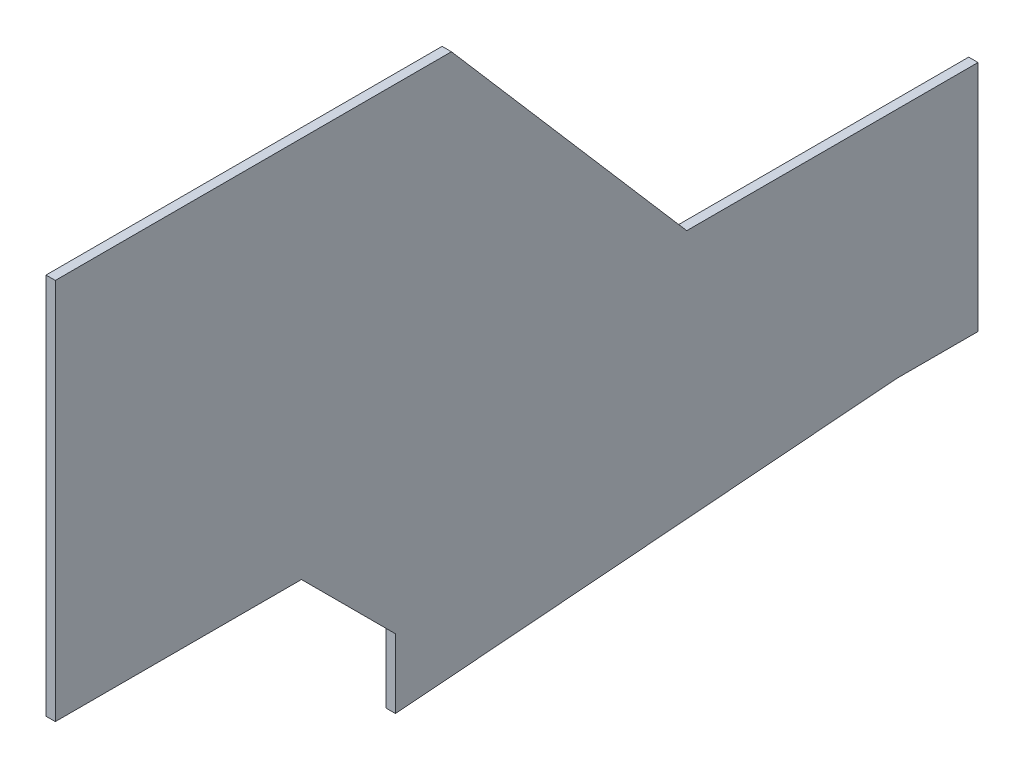
SolidWorks part; units mm, degrees
ref_plane "Alzado" through (0, 0, 0) normal (0, 0, 1) x (1, 0, 0)
ref_plane "Planta" through (0, 0, 0) normal (0, 1, 0) x (1, 0, 0)
ref_plane "Vista lateral" through (0, 0, 0) normal (1, 0, 0) x (0, 0, -1)
sketch "Croquis2" plane through (0, 0, 0) normal (1, 0, 0) x (0, 0, -1)
  line L0 (-196, -75) -> (-90.3534, -75)
  line L1 (-200, 150) -> (200, 150) construction
  line L2 (-200, 150) -> (-200, -150) construction
  line L3 (-200, -150) -> (200, -150) construction
  line L4 (200, 150) -> (200, -150) construction
  line L5 (-200, 150) -> (200, -150) construction
  line L6 (-200, -150) -> (200, 150) construction
  line L11 (-90.3534, -75) -> (-28.5398, -75) construction
  line L12 (-150, -75) -> (-150, -79) construction
  line L17 (-90.3534, -75) -> (-50, -115.3534)
  line L18 (-50, -115.3534) -> (-50, -145)
  line L19 (-50, -145) -> (165, -128)
  line L20 (165, -128) -> (200, -128)
  line L21 (200, -128) -> (200, -28)
  line L22 (200, -28) -> (75, -28)
  line L23 (75, -28) -> (-26, 89)
  line L24 (-26, 89) -> (-196, 89)
  line L25 (-196, 89) -> (-196, -75)
  line L26 (-150, -79) -> (-100, -79) construction
  line L27 (-100, -79) -> (-100, -75) construction
  point P0 (0, 0)
  point P9 (-98.3041, -71)
  point P10 (2, 0)
  dimension "D1" = 400
  dimension "D2" = 300
  dimension "D3" = 4
  dimension "D4" = 75
  dimension "D6" = 22
  dimension "D7" = 35
  dimension "D5" = 5
  dimension "D8" = 150
  dimension "D9" = 45
  dimension "D10" = 100
  dimension "D11" = 170
  dimension "D12" = 275
  dimension "D13" = 164
  dimension "D14" = 50
  dimension "D15" = 4
  dimension "D16" = 50
extrude "Saliente-Extruir1" add sketch "Croquis2" along normal blind 4
equation "\"venesta\"= 4'grosor de la venesta"
equation "\"policarbonato\"= 4'grosor del policarbonato"
equation "\"carton_trupan\"= 3'grosor del carton trupan caso laser"
equation "\"ancho_tot\"= 310'ancho tot sin llantas"
equation "\"largo_tot\"= 400'largo tot sin camera"
equation "\"alto_estimado\"= 300'alto estimado sin lidar"
equation "\"D2@Croquis2\"=\"alto_estimado\""
equation "\"D1@Croquis2\"=\"largo_tot\""
equation "\"altoparaqpaselabotella\"= 75'alto estimado para que encaje la botella"
equation "\"alturaruedaloca\"= 22"
equation "\"anchoruedaloca\"= 35"
equation "\"anchopiso1motorybaterias\"= 150"
equation "\"dist-pisorampa\"= 5"
equation "\"D3@Croquis2\"=\"venesta\""
equation "\"D4@Croquis2\"=\"altoparaqpaselabotella\""
equation "\"D6@Croquis2\"=\"alturaruedaloca\""
equation "\"D7@Croquis2\"=\"anchoruedaloca\""
equation "\"D5@Croquis2\"=\"dist-pisorampa\""
equation "\"D8@Croquis2\"=\"anchopiso1motorybaterias\""
equation "\"D10@Croquis2\"= \"paredtrasera\""
equation "\"D11@Croquis2\" = \"anchoultimopiso\""
equation "\"anchoultimopiso\"= 170"
equation "\"paredtrasera\"= 100"
equation "\"agarradorcanasta\"= 275'recolector"
equation "\"D12@Croquis2\"=\"agarradorcanasta\""
equation "\"D13@Croquis2\"= \"alturapiso1y2\" + \"venesta\" + \"alturapiso2y3\""
equation "\"alturapiso1y2\"= 80"
equation "\"alturapiso2y3\"= 80"
equation "\"D1@Saliente-Extruir1\"=\"policarbonato\""
equation "\"D15@Croquis2\"=\"venesta\""
